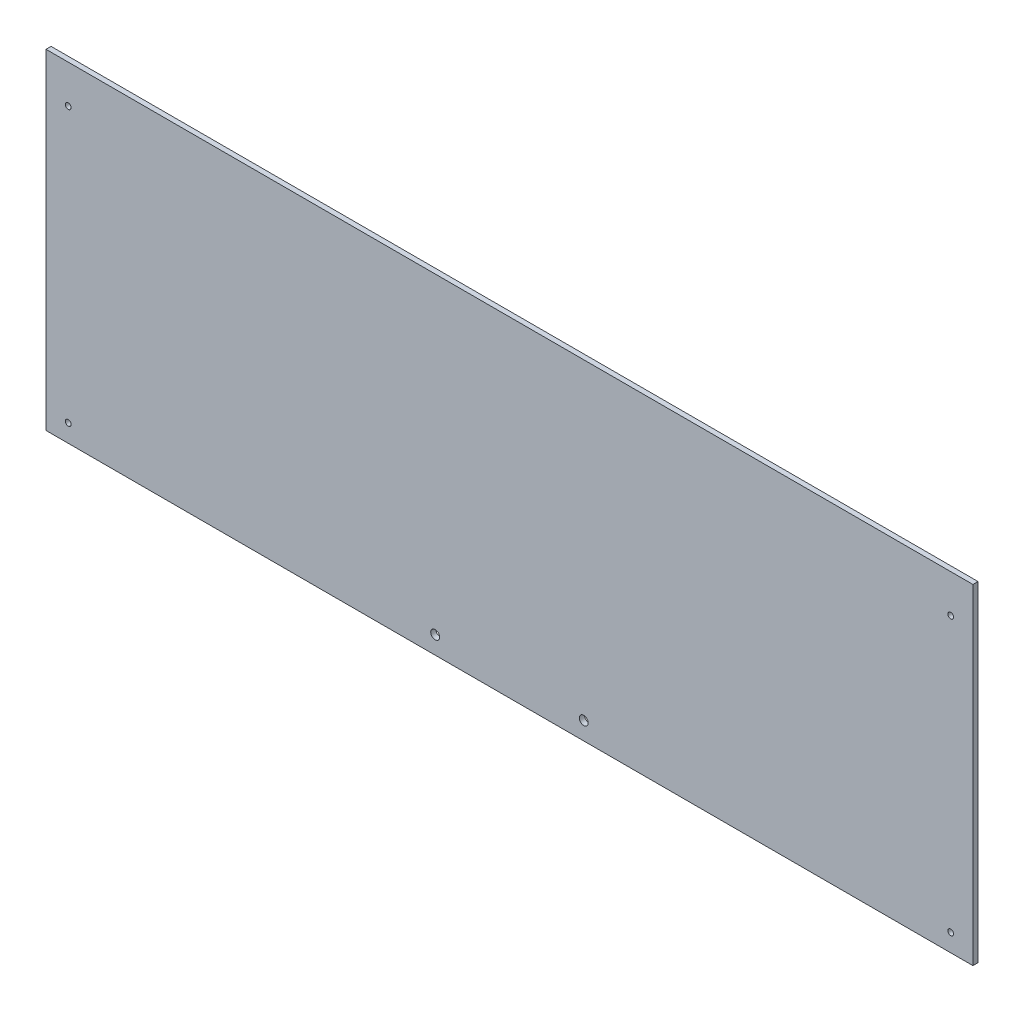
SolidWorks part; units mm, degrees
material "PC"
ref_plane "Front Plane" through (0, 0, 0) normal (0, 0, 1) x (1, 0, 0)
ref_plane "Top Plane" through (0, 0, 0) normal (0, 1, 0) x (1, 0, 0)
ref_plane "Right Plane" through (0, 0, 0) normal (1, 0, 0) x (0, 0, -1)
sketch "Sketch1" plane through (0, 0, 0) normal (0, 0, 1) x (1, 0, 0)
  line L1 (-365, 0) -> (365, 0)
  line L2 (-365, 0) -> (-365, -260)
  line L3 (-365, -260) -> (365, -260)
  line L4 (365, 0) -> (365, -260)
  dimension "D1" = 730
  dimension "D2" = 260
extrude "Boss-Extrude1" add sketch "Sketch1" along normal mid plane 4
sketch "Sketch2" plane through (0, 0, 2) normal (0, 0, 1) x (1, 0, 0)
  line L0 (-365, 0) -> (-365, -260) construction
  line L1 (365, 0) -> (-365, 0) construction
  line L2 (-347.5, -246) -> (-347.5, -30) construction
  line L3 (-365, -260) -> (365, -260) construction
  line L4 (0, 0) -> (0, -232.7726) construction
  circle A0 centre (-347.5, -30) radius 2.25
  circle A1 centre (-347.5, -246) radius 2.25
  circle A2 centre (-58.5, -246) radius 3.5
  circle A3 centre (58.5, -246) radius 3.5
  circle A4 centre (347.5, -246) radius 2.25
  circle A5 centre (347.5, -30) radius 2.25
  dimension "D1" = 4.5
  dimension "D4" = 14
  dimension "D5" = 7
  dimension "D7" = 117
  dimension "D2" = 17.5
  dimension "D3" = 30
  dimension "D6" = 14
extrude "Cut-Extrude1" cut sketch "Sketch2" against normal through all
